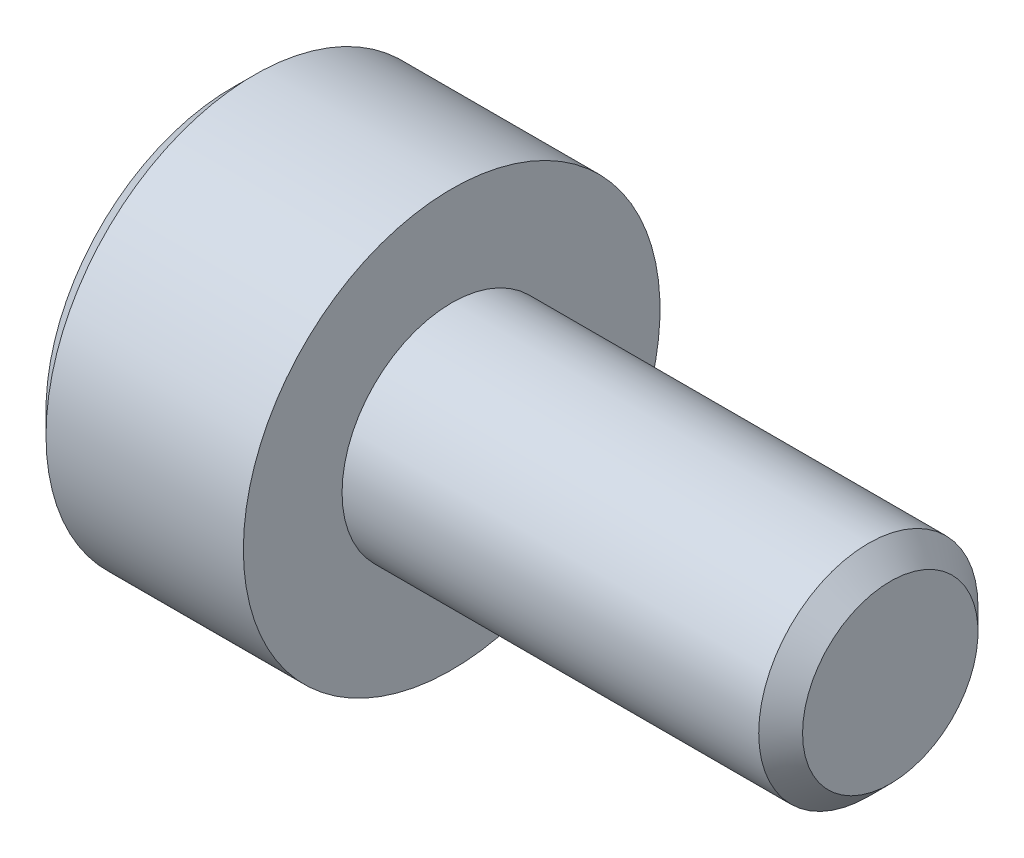
SolidWorks part; units mm, degrees
material "Plain Carbon Steel"
ref_plane "Front Plane" through (0, 0, 0) normal (0, 0, 1) x (1, 0, 0)
ref_plane "Top Plane" through (0, 0, 0) normal (0, 1, 0) x (1, 0, 0)
ref_plane "Right Plane" through (0, 0, 0) normal (1, 0, 0) x (0, 0, -1)
sketch "Sketch1" plane through (0, 0, 0) normal (0, 0, 1) x (1, 0, 0)
  line L0 (0, 0) -> (6, 0) construction
  line L1 (6, 0) -> (6, 1)
  line L2 (6, 1) -> (2, 1)
  line L3 (2, 1) -> (2, 1.9)
  line L4 (2, 1.9) -> (0, 1.9)
  line L5 (0, 1.9) -> (0, 0)
  line L6 (0, 0) -> (6, 0)
  dimension "D1" = 1.9
  dimension "D2" = 2
  dimension "D3" = 1
  dimension "D4" = 4
revolve "Revolve1" add sketch "Sketch1" angle 360 about L0
sketch "Sketch2" plane through (0, 0, 0) normal (-1, 0, 0) x (0, 0, 1)
  line L1 (0.6402, -1.1089) -> (1.2805, 0)
  line L2 (1.2805, 0) -> (0.6402, 1.1089)
  line L3 (0.6402, 1.1089) -> (-0.6402, 1.1089)
  line L4 (-0.6402, 1.1089) -> (-1.2805, 0)
  line L5 (-1.2805, 0) -> (-0.6402, -1.1089)
  line L6 (-0.6402, -1.1089) -> (0.6402, -1.1089)
  circle A0 centre (0, 0) radius 1.1089 construction
extrude "Cut-Extrude1" cut sketch "Sketch2" against normal blind 1.27
chamfer "Chamfer1" distance 0.2 angle 45 2 edges at (6, 0, 1) (0, 0, 1.9)
